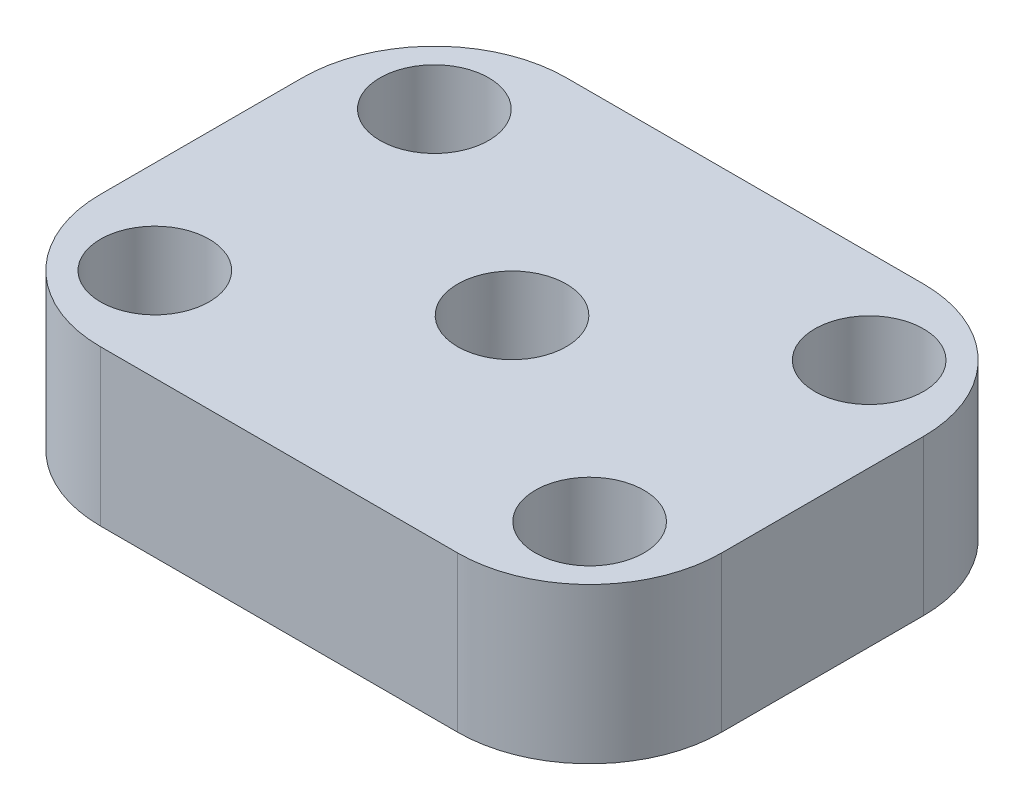
SolidWorks part; units mm, degrees
ref_plane "Front Plane" through (0, 0, 0) normal (0, 0, 1) x (1, 0, 0)
ref_plane "Top Plane" through (0, 0, 0) normal (0, 1, 0) x (1, 0, 0)
ref_plane "Right Plane" through (0, 0, 0) normal (1, 0, 0) x (0, 0, -1)
sketch "Sketch1" plane through (0, 0, 0) normal (0, 1, 0) x (1, 0, 0)
  line L1 (-20, 15) -> (20, 15)
  line L2 (-20, 15) -> (-20, -15)
  line L3 (-20, -15) -> (20, -15)
  line L4 (20, 15) -> (20, -15)
  line L5 (-20, 15) -> (20, -15) construction
  line L6 (-20, -15) -> (20, 15) construction
  point P0 (0, 0)
  dimension "D1" = 30
  dimension "D2" = 40
extrude "Boss-Extrude1" add sketch "Sketch1" along normal blind 10
sketch "Sketch3" plane through (0, 0, 0) normal (0, -1, 0) x (1, 0, 0)
  circle A0 centre (0, 0) radius 6.625
  dimension "D1" = 13.25
extrude "Cut-Extrude1" cut sketch "Sketch3" against normal blind 4.5
sketch "Sketch4" plane through (0, 10, 0) normal (0, 1, 0) x (1, 0, 0)
  circle A0 centre (0, 0) radius 3.5
  dimension "D1" = 7
extrude "Cut-Extrude2" cut sketch "Sketch4" against normal through all
hole_wizard "Ø3.0mm Dowel Hole1" positions "Sketch7" profile "Sketch8" hole size "Ø3.0" standard "ANSI Metric" end condition up to next
sketch "Sketch7" plane through (0, 10, 0) normal (0, 1, 0) x (1, 0, 0)
  line L0 (20, 0) -> (-20, 0) construction
  line L1 (20, -15) -> (20, 15) construction
  line L2 (-20, 15) -> (-20, -15) construction
  line L4 (0, 15) -> (0, -15) construction
  line L5 (20, 15) -> (-20, 15) construction
  line L6 (-20, -15) -> (20, -15) construction
  point P0 (-14, 9)
  point P21 (-14, -9)
  point P22 (14, -9)
  point P23 (14, 9)
  dimension "D1" = 6
  dimension "D2" = 6
sketch "Sketch8" plane through (-14, 10, -9) normal (1, 0, 0) x (0, 0, 1)
  line L0 (0, 0) -> (0, 10)
  line L1 (0, 10) -> (1.5, 10)
  line L2 (1.5, 10) -> (1.5, 0)
  line L5 (1.5, 0) -> (0, 0)
  line L11 (0, -6.35) -> (0, 107.95) construction
  dimension "Thru Hole Dia." = 3
  dimension "Thru Hole Depth" = 10
fillet "Fillet1" radius 8.5 4 edges at (20, 5, -15) (20, 5, 15) (-20, 5, 15) (-20, 5, -15)
sketch "Sketch9" plane through (0, 10, 0) normal (0, 1, 0) x (1, 0, 0)
  line L0 (14, -9) -> (-14, -9) construction
  circle A0 centre (14, -9) radius 3.5
  circle A1 centre (-14, -9) radius 3.5
  circle A2 centre (-14, 9) radius 3.5
  circle A3 centre (14, 9) radius 3.5
  dimension "D1" = 7
  dimension "D4" = 28
  dimension "D5" = 18
  dimension "D2" = 2
  dimension "D3" = 2
extrude "Cut-Extrude3" cut sketch "Sketch9" against normal blind 5
